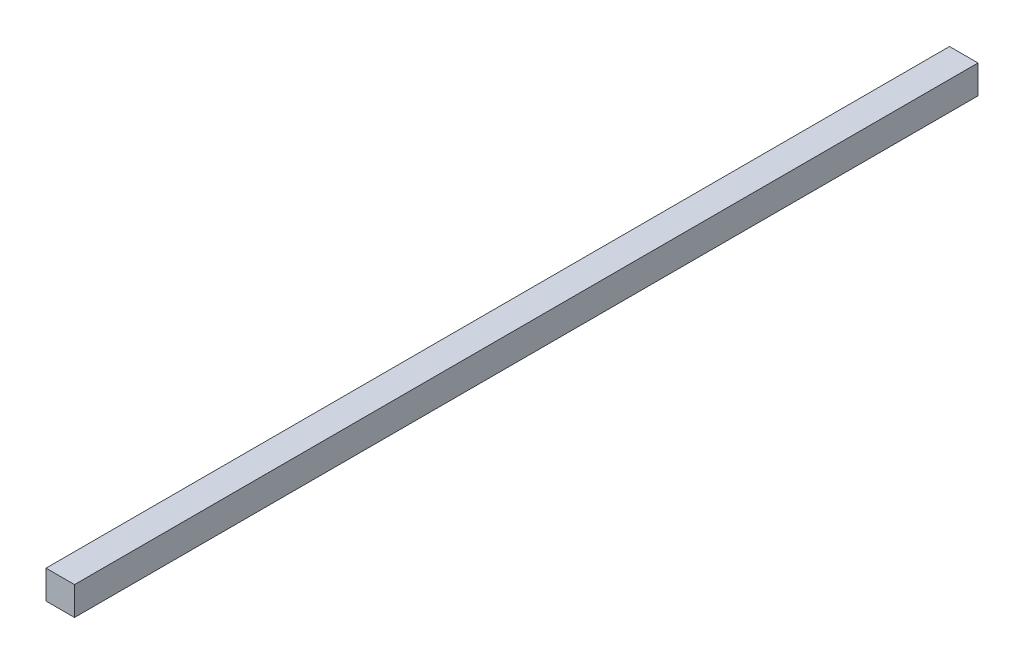
SolidWorks part; units mm, degrees
ref_plane "Front Plane" through (0, 0, 0) normal (0, 0, 1) x (1, 0, 0)
ref_plane "Top Plane" through (0, 0, 0) normal (0, 1, 0) x (1, 0, 0)
ref_plane "Right Plane" through (0, 0, 0) normal (1, 0, 0) x (0, 0, -1)
sketch "Sketch1" plane through (0, 0, 0) normal (0, 0, 1) x (1, 0, 0)
  line L1 (65.674, 50.8) -> (91.074, 50.8)
  line L2 (65.674, 50.8) -> (65.674, 25.4)
  line L3 (65.674, 25.4) -> (91.074, 25.4)
  line L4 (91.074, 50.8) -> (91.074, 25.4)
  dimension "D1" = 25.4
  dimension "D2" = 25.4
extrude "Extrude1" add sketch "Sketch1" along normal up to surface (805.18 mm away)
